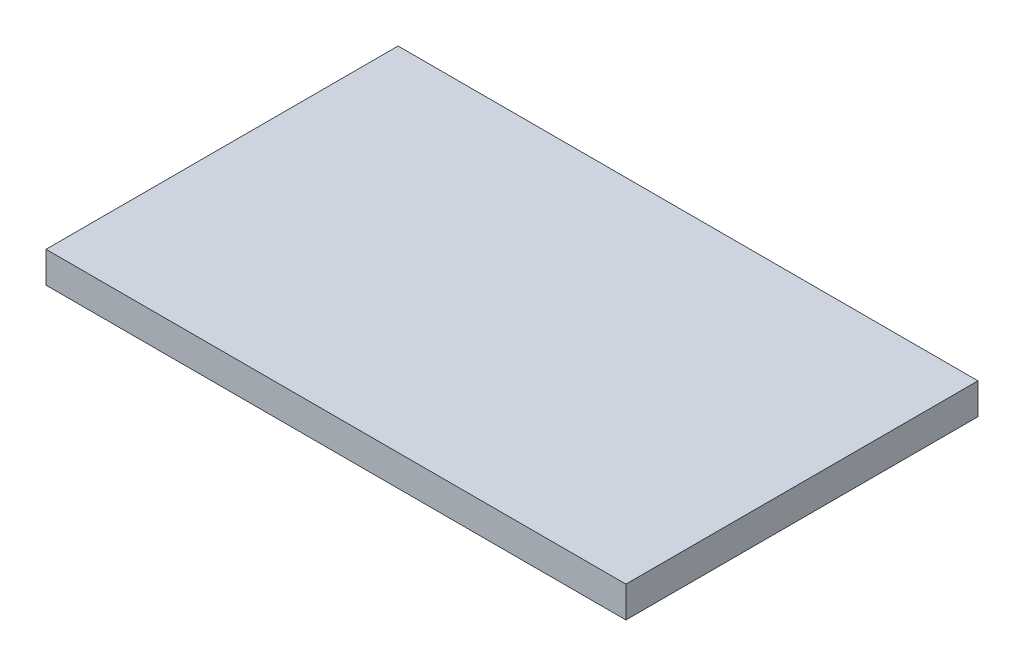
SolidWorks part; units mm, degrees
ref_plane "Front" through (0, 0, 0) normal (0, 0, 1) x (1, 0, 0)
ref_plane "Top" through (0, 0, 0) normal (0, 1, 0) x (1, 0, 0)
ref_plane "Right" through (0, 0, 0) normal (1, 0, 0) x (0, 0, -1)
sketch "Sketch1" plane through (0, 0, 0) normal (0, 0, 1) x (1, 0, 0)
  line L1 (-84, -4.5) -> (84, -4.5)
  line L2 (-84, -4.5) -> (-84, 4.5)
  line L3 (-84, 4.5) -> (84, 4.5)
  line L4 (84, -4.5) -> (84, 4.5)
  line L5 (-84, -4.5) -> (84, 4.5) construction
  line L6 (-84, 4.5) -> (84, -4.5) construction
  point P0 (0, 0)
  dimension "D1" = 9
  dimension "D2" = 168
extrude "Boss-Extrude1" add sketch "Sketch1" along normal blind 102
